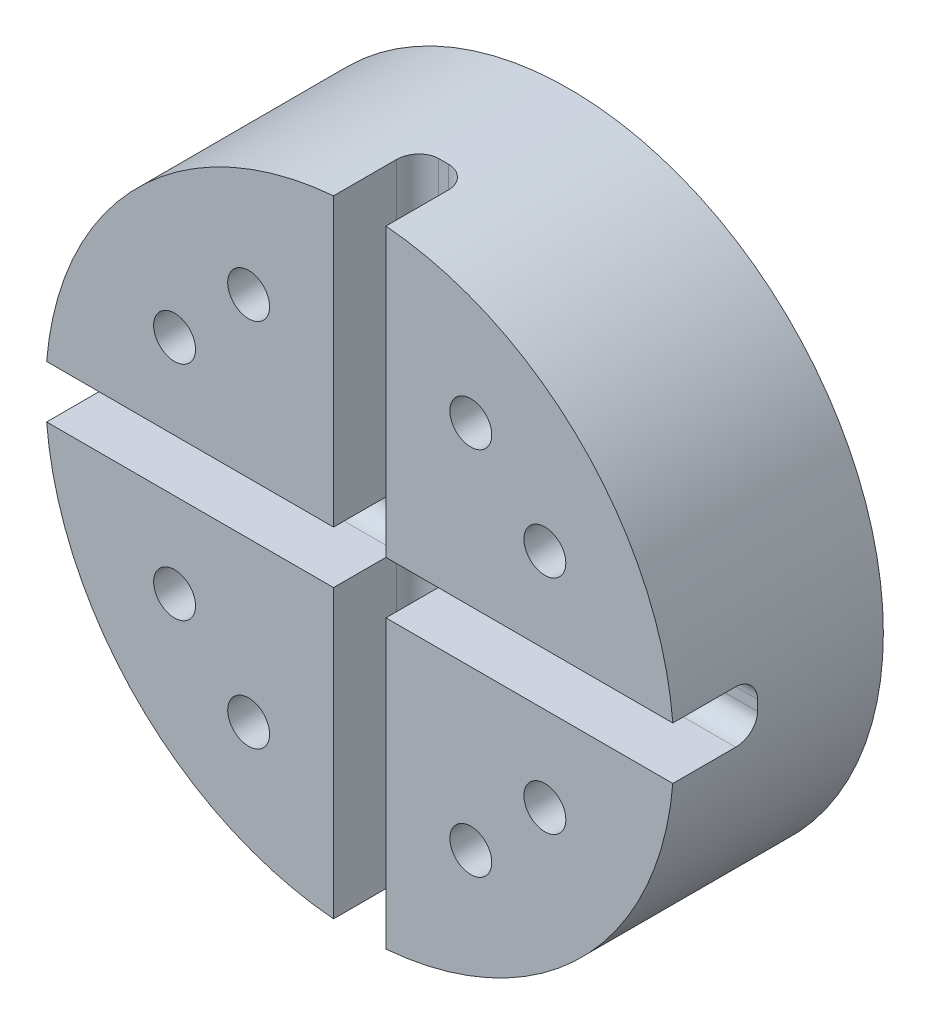
SolidWorks part; units mm, degrees
ref_plane "Front Plane" through (0, 0, 0) normal (0, 0, 1) x (1, 0, 0)
ref_plane "Top Plane" through (0, 0, 0) normal (0, 1, 0) x (1, 0, 0)
ref_plane "Right Plane" through (0, 0, 0) normal (1, 0, 0) x (0, 0, -1)
sketch "Sketch2" plane through (0, 0, 0) normal (0, 0, 1) x (1, 0, 0)
  circle A0 centre (0, 0) radius 15
  dimension "D1" = 30
extrude "Boss-Extrude1" add sketch "Sketch2" along normal blind 10
sketch "Sketch3" plane through (0, 0, 10) normal (0, 0, 1) x (1, 0, 0)
  line L5 (-1.25, 1.25) -> (-1.25, 15.296)
  line L6 (1.25, 1.25) -> (1.25, 15.296)
  line L7 (-1.25, 15.296) -> (1.25, 15.296)
  line L9 (1.25, 1.25) -> (15.6747, 1.25)
  line L10 (1.25, -1.25) -> (15.6747, -1.25)
  line L11 (15.6747, 1.25) -> (15.6747, -1.25)
  line L13 (1.25, -1.25) -> (1.25, -15.6292)
  line L14 (-1.25, -1.25) -> (-1.25, -15.6292)
  line L15 (1.25, -15.6292) -> (-1.25, -15.6292)
  line L17 (-1.25, 1.25) -> (-15.4105, 1.25)
  line L18 (-1.25, -1.25) -> (-15.4105, -1.25)
  line L19 (-15.4105, 1.25) -> (-15.4105, -1.25)
extrude "Cut-Extrude1" cut sketch "Sketch3" against normal blind 4
fillet "Fillet1" radius 1 8 edges at (-1.25, -8.0989, 6) (1.25, -8.0989, 6) (8.0989, -1.25, 6) (8.0989, 1.25, 6) (1.25, 8.0989, 6) (-1.25, 8.0989, 6) (-8.0989, -1.25, 6) (-8.0989, 1.25, 6)
sketch "Sketch4" plane through (0, 0, 10) normal (0, 0, 1) x (1, 0, 0)
  line L0 (0, 0) -> (-10.6066, 10.6066) construction
  line L1 (-5.3033, 5.3033) -> (-5.3033, 8.8388) construction
  line L2 (-5.3033, 5.3033) -> (-8.8388, 5.3033) construction
  line L6 (-8.8388, 5.3033) -> (-5.3033, 8.8388) construction
  arc A3 (-1.25, 14.9478) -> (-14.9478, 1.25) centre (0, 0) ccw construction
  circle A4 centre (-8.8388, 5.3033) radius 1
  circle A5 centre (-5.3033, 8.8388) radius 1
  dimension "D2" = 2
  dimension "D1" = 5
extrude "Cut-Extrude2" cut sketch "Sketch4" against normal up to surface (10 mm away) contours A5 | A4 up to face at (15, 0, 0)
pattern_circular "CirPattern1" count 4 every 90 about axis through (0, 0, 0) along (0, 0, 1) of "Cut-Extrude2"
